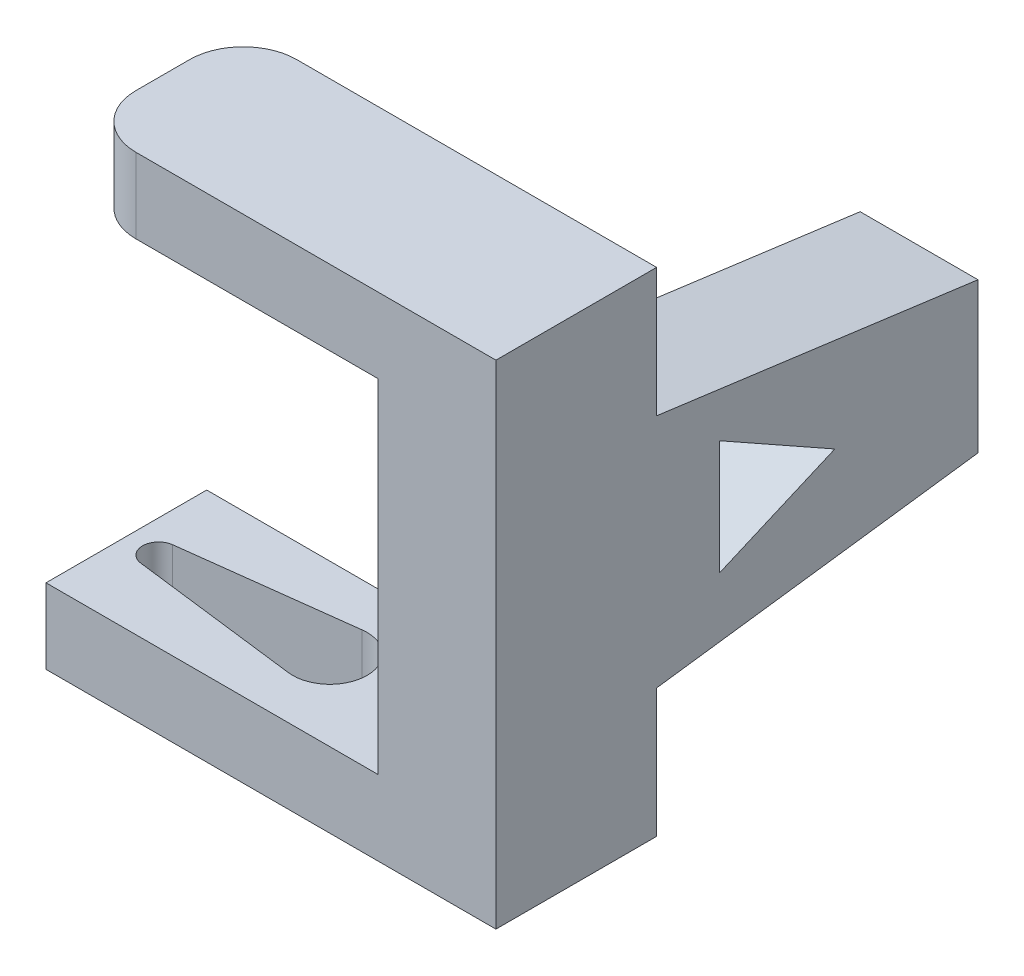
SolidWorks part; units mm, degrees
ref_plane "前视基准面" through (0, 0, 0) normal (0, 0, 1) x (1, 0, 0)
ref_plane "上视基准面" through (0, 0, 0) normal (0, 1, 0) x (1, 0, 0)
ref_plane "右视基准面" through (0, 0, 0) normal (1, 0, 0) x (0, 0, -1)
sketch "草图1" plane through (0, 0, 0) normal (0, 0, 1) x (1, 0, 0)
  line L1 (0, 0) -> (13, 0)
  line L2 (0, 0) -> (0, -38)
  line L3 (0, -38) -> (13, -38)
  line L4 (13, 0) -> (13, -38)
  line L5 (-8, -3) -> (8, -3)
  line L6 (-8, -3) -> (-8, -35)
  line L7 (-8, -35) -> (8, -35)
  line L8 (8, -3) -> (8, -35)
  line L9 (-8, -3) -> (8, -35) construction
  line L10 (-8, -35) -> (8, -3) construction
  point P5 (0, -19)
  dimension "D1" = 38
  dimension "D2" = 16
  dimension "D3" = 32
  dimension "D4" = 13
extrude "凸台-拉伸1" add sketch "草图1" along normal blind 15 contours L5 L8 L7 L2 L3 L4 L1
sketch "草图2" plane through (0, -38, 0) normal (0, -1, 0) x (1, 0, 0)
  line L0 (0, 15) -> (0, 0)
  line L1 (0, 0) -> (0, 7.5)
  line L2 (0, 7.5) -> (4, 7.5)
  circle A0 centre (4, 7.5) radius 3.475
  dimension "D2" = 6.95
  dimension "D1" = 4
sketch "草图3" plane through (0, 0, 0) normal (-1, 0, 0) x (0, 0, 1)
  line L0 (0, 0) -> (0, -3)
  line L4 (15, -38) -> (0, -38) construction
  line L5 (0, 0) -> (15, 0)
  line L6 (0, 0) -> (0, -3)
  line L7 (0, -3) -> (15, -3)
  line L8 (15, 0) -> (15, -3)
  line L9 (0, -35) -> (15, -35)
  line L10 (0, -35) -> (0, -38)
  line L11 (0, -38) -> (15, -38)
  line L12 (15, -35) -> (15, -38)
  line L13 (15, -35) -> (15, -38) construction
extrude "凸台-拉伸2" add sketch "草图3" along normal blind 15 contours L12 L9 L10 L11
sketch "草图4" plane through (0, -38, 0) normal (0, -1, 0) x (1, 0, 0)
  line L1 (-12.1703, 8.9885) -> (3.5707, 10.9484)
  line L2 (-12.1703, 6.0115) -> (3.5707, 4.0516)
  arc A0 (3.5707, 4.0516) -> (3.5707, 10.9484) centre (4, 7.5) ccw
  arc A1 (-12.1703, 8.9885) -> (-12.1703, 6.0115) centre (-11.985, 7.5) ccw
  dimension "D2" = 3
extrude "切除-拉伸1" cut sketch "草图4" against normal blind 15
sketch "草图5" plane through (13, 0, 0) normal (1, 0, 0) x (0, 0, -1)
  line L1 (-15, 0) -> (0, 0)
  line L2 (-15, 0) -> (-15, -38)
  line L3 (-15, -38) -> (0, -38)
  line L4 (0, 0) -> (0, -38)
extrude "凸台-拉伸3" add sketch "草图5" along normal blind 10
sketch "草图6" plane through (0, 0, 15) normal (0, 0, 1) x (1, 0, 0)
  line L0 (8, -3) -> (8, -35)
  line L1 (8, -3) -> (16, -3)
  line L2 (8, -35) -> (16, -35)
  line L3 (16, -3) -> (16, -35)
  dimension "D1" = 8
extrude "切除-拉伸2" cut sketch "草图6" against normal blind 22
sketch "草图7" plane through (0, 0, 0) normal (0, 0, -1) x (-1, 0, 0)
  line L0 (-23, 0) -> (-23, -38) construction
  line L1 (-23, -38) -> (-23, -19) construction
  line L2 (-23, -19) -> (-16, -19) construction
  line L3 (-16, -35) -> (-16, -3) construction
  line L4 (-16, -19) -> (-19.5, -19) construction
  line L6 (-23, -30) -> (-16, -30)
  line L7 (-23, -30) -> (-23, -8)
  line L8 (-23, -8) -> (-16, -8)
  line L9 (-16, -30) -> (-16, -8)
  line L10 (-23, -30) -> (-16, -8) construction
  line L11 (-23, -8) -> (-16, -30) construction
  dimension "D1" = 22
extrude "凸台-拉伸4" add sketch "草图7" along normal blind 30
sketch "草图8" plane through (23, 0, 0) normal (1, 0, 0) x (0, 0, -1)
  line L0 (30, -30) -> (30, -8)
  line L1 (30, -8) -> (30, -19)
  line L2 (30, -19) -> (30, -12)
  line L3 (0, -8) -> (30, -12)
  line L4 (30, -19) -> (30, -26)
  line L5 (0, -30) -> (30, -26)
  line M5 (0, -30) -> (30, -30)
  line M6 (30, -30) -> (30, -8)
  line M7 (30, -8) -> (0, -8)
  dimension "D1" = 7
  dimension "D2" = 7
extrude "切除-拉伸3" cut sketch "草图8" against normal blind 30 contours L3 L1 M7 | L5 M5 M6
sketch "草图9" plane through (23, 0, 0) normal (1, 0, 0) x (0, 0, -1)
  line L0 (0, -8) -> (0, -30)
  line L1 (0, -30) -> (0, -19)
  line L2 (0, -19) -> (5.8667, -19)
  line L3 (5.8667, -19) -> (5.8667, -12.9506)
  line L4 (5.8667, -12.9506) -> (5.8667, -23.6412)
  line L5 (5.8667, -23.6412) -> (5.8667, -19)
  line L6 (16.6316, -19) -> (5.8667, -12.9506)
  line L7 (5.8667, -23.6412) -> (16.6316, -19)
extrude "切除-拉伸4" cut sketch "草图9" against normal blind 30 contours L4 L7 L6 L3
sketch "草图10" plane through (0, 0, 0) normal (0, 1, 0) x (1, 0, 0)
  line L0 (-15, 0) -> (-15, -15)
  line L1 (-15, 0) -> (-11.5943, 0)
  line L2 (-15, -15) -> (-11.5943, -15)
  line L3 (-11.5943, 0) -> (-11.5943, -15)
extrude "切除-拉伸5" cut sketch "草图10" against normal blind 10
sketch "草图11" plane through (0, 0, 0) normal (0, 1, 0) x (1, 0, 0)
  line L0 (23, 0) -> (-6.5943, 0)
  line L1 (-15, 0) -> (16, 0) construction
  line L2 (-11.5943, -15) -> (-11.5943, 0) construction
  line L3 (-11.5943, -5) -> (-11.5943, -10)
  line L4 (-6.5943, -15) -> (23, -15)
  line L5 (-6.5943, 0) -> (-22.7429, 0.592)
  line L6 (-22.7429, 0.592) -> (-20.7594, -5)
  line L7 (-20.7594, -5) -> (-11.5943, -5)
  line L8 (-11.5943, -10) -> (-29.8808, -20.0774)
  line L9 (-29.8808, -20.0774) -> (-15.6989, -24.1819)
  line L10 (-15.6989, -24.1819) -> (-6.5943, -15)
  arc A0 (-11.5943, -10) -> (-6.5943, -15) centre (-6.5943, -10) ccw
  arc A1 (-6.5943, 0) -> (-11.5943, -5) centre (-6.5943, -5) ccw
  point P13 (-11.5943, -15)
  point P16 (-11.5943, 0)
  line M1 (-11.5943, 0) -> (-11.5943, -15)
  line M2 (-11.5943, -15) -> (23, -15)
  line M4 (23, 0) -> (-11.5943, 0)
  dimension "D1" = 5
  dimension "D2" = 5
extrude "切除-拉伸6" cut sketch "草图11" against normal blind 10 contours A0 M1 M2 | A1 M4 M1
sketch "草图12" plane through (0, -38, 0) normal (0, -1, 0) x (-1, 0, 0)
  line L1 (-23, 0) -> (15, 0)
  line L2 (-23, 0) -> (-23, -15)
  line L3 (-23, -15) -> (15, -15)
  line L4 (15, 0) -> (15, -15)
  line L5 (11.985, -6) -> (-3.5707, -4.0516)
  line L6 (12.1703, -6.0115) -> (-3.5707, -4.0516) construction
  line L7 (-3.5707, -10.9484) -> (11.985, -9)
  circle A0 centre (-4, -7.5) radius 3.475
  circle A2 centre (11.985, -7.5) radius 1.5
  line M2 (-3.5707, -4.0516) -> (12.1703, -6.0115)
  arc M3 (12.1703, -6.0115) -> (12.1703, -8.9885) centre (11.985, -7.5) cw
  line M4 (12.1703, -8.9885) -> (-3.5707, -10.9484)
  arc M5 (-3.5707, -10.9484) -> (-3.5707, -4.0516) centre (-4, -7.5) cw
  line M6 (15, 0) -> (-23, 0)
  line M7 (-23, 0) -> (-23, -15)
  line M8 (-23, -15) -> (15, -15)
  line M9 (15, -15) -> (15, 0)
extrude "凸台-拉伸5" add sketch "草图12" along normal blind 4 separate body contours M9 M6 M7 M8 M5 M2 M3 M4
sketch "草图13" plane through (0, 0, 0) normal (0, 1, 0) x (1, 0, 0)
  line L0 (-6.5943, -15) -> (23, -15) construction
  line L1 (-6.5943, 0) -> (23, 0)
  line L2 (-6.5943, 0) -> (-6.5943, -15)
  line L3 (-6.5943, -15) -> (23, -15)
  line L4 (23, 0) -> (23, -15)
  line L5 (23, 0) -> (23, -15) construction
  line L6 (-11.5943, -10) -> (-11.5943, -5) construction
  line L7 (-11.5943, -5) -> (-11.5943, -10)
  arc A0 (-6.5943, 0) -> (-11.5943, -5) centre (-6.5943, -5) ccw
  arc A1 (-11.5943, -10) -> (-6.5943, -15) centre (-6.5943, -10) ccw
  line M1 (-11.5943, -5) -> (-11.5943, -10)
  arc M2 (-11.5943, -10) -> (-6.5943, -15) centre (-6.5943, -10) ccw
  line M3 (-6.5943, -15) -> (23, -15)
  line M4 (23, -15) -> (23, 0)
  line M5 (23, 0) -> (-6.5943, 0)
  arc M6 (-6.5943, 0) -> (-11.5943, -5) centre (-6.5943, -5) ccw
extrude "凸台-拉伸6" add sketch "草图13" along normal blind 4 contours L2 M6 M1 M2 | L2 M5 M3 M4
sketch "草图14" plane through (23, 0, 0) normal (1, 0, 0) x (0, 0, -1)
  line L0 (0, -42) -> (0, -38) construction
  line L1 (-15, 4) -> (0, 4)
  line L2 (-15, 4) -> (-15, -42)
  line L3 (-15, -42) -> (0, -42)
  line L4 (0, 4) -> (0, -42)
extrude "凸台-拉伸7" add sketch "草图14" along normal blind 4
sketch "草图15" plane through (23, 0, 0) normal (1, 0, 0) x (0, 0, -1)
  line L0 (0, -8) -> (0, -30)
  line L1 (0, -30) -> (30, -26)
  line L2 (30, -26) -> (30, -12)
  line L3 (30, -12) -> (0, -8)
  line L4 (5.8667, -12.9506) -> (5.8667, -23.6412)
  line L5 (5.8667, -23.6412) -> (16.6316, -19) construction
  line L6 (5.8667, -12.9506) -> (5.8667, -23.6412) construction
  line L7 (5.8667, -23.6412) -> (16.6316, -19)
  line L8 (16.6316, -19) -> (5.8667, -12.9506)
extrude "凸台-拉伸9" add sketch "草图15" along normal blind 4 contours L3 L0 L1 L2 | L8 L4 L7
